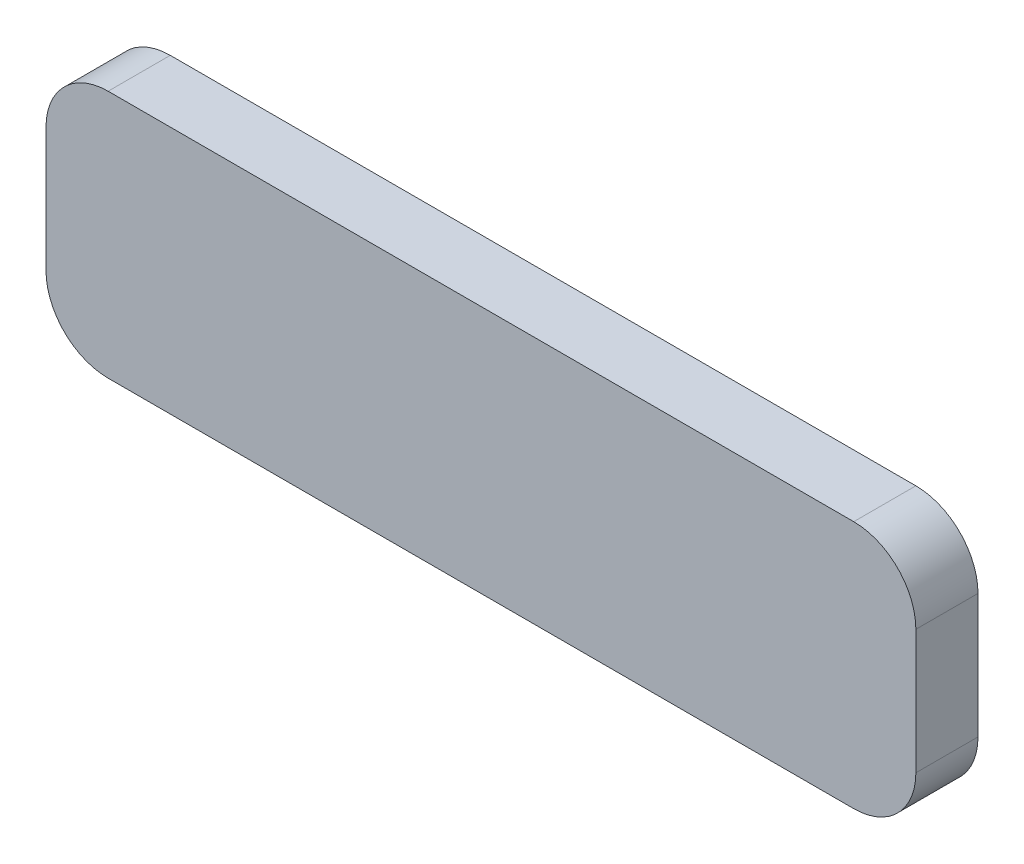
SolidWorks part; units mm, degrees
material "Benutzerdefinierter Kunststoff"
ref_plane "Ebene vorne" through (0, 0, 0) normal (0, 0, 1) x (1, 0, 0)
ref_plane "Ebene oben" through (0, 0, 0) normal (0, 1, 0) x (1, 0, 0)
ref_plane "Ebene rechts" through (0, 0, 0) normal (1, 0, 0) x (0, 0, -1)
sketch "Skizze1" plane through (0, 0, 0) normal (0, 0, 1) x (1, 0, 0)
  line L1 (1, 0) -> (13, 0)
  line L2 (0, 1) -> (0, 3)
  line L3 (1, 4) -> (13, 4)
  line L4 (14, 1) -> (14, 3)
  arc A0 (1, 0) -> (0, 1) centre (1, 1) cw
  arc A1 (0, 3) -> (1, 4) centre (1, 3) cw
  arc A2 (13, 4) -> (14, 3) centre (13, 3) cw
  arc A3 (14, 1) -> (13, 0) centre (13, 1) cw
  point P7 (0, 0)
  point P10 (0, 4)
  point P15 (14, 0)
  dimension "D3" = 1
  dimension "D1" = 14
  dimension "D2" = 4
extrude "Aufsatz-Linear austragen1" add sketch "Skizze1" along normal blind 1
